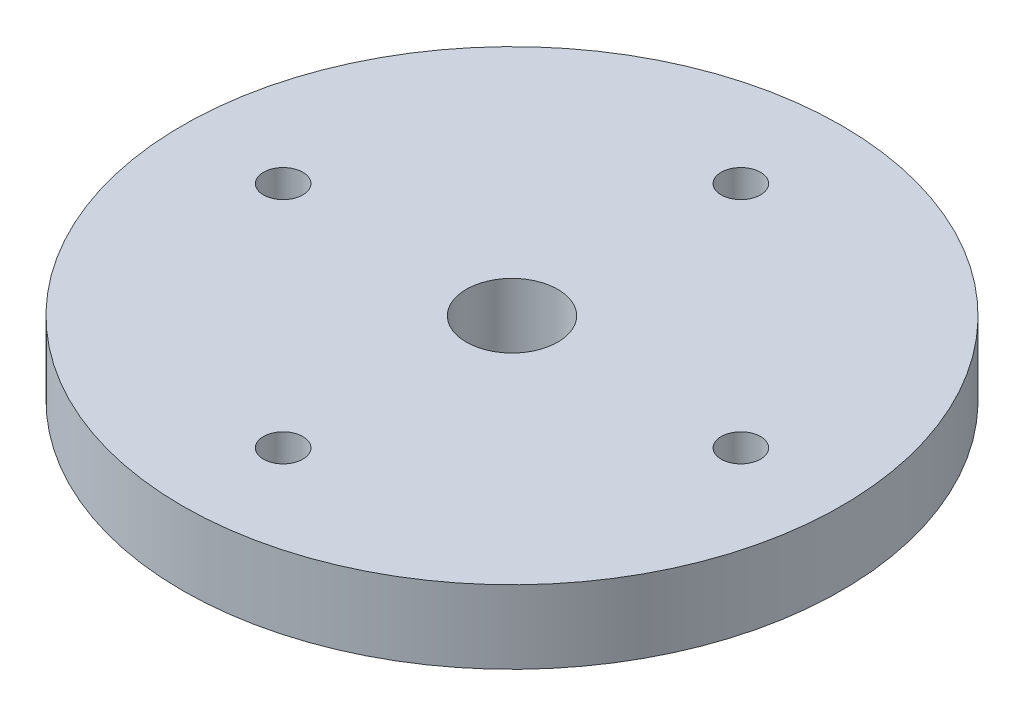
SolidWorks part; units mm, degrees
ref_plane "前视基准面" through (0, 0, 0) normal (0, 0, 1) x (1, 0, 0)
ref_plane "上视基准面" through (0, 0, 0) normal (0, 1, 0) x (1, 0, 0)
ref_plane "右视基准面" through (0, 0, 0) normal (1, 0, 0) x (0, 0, -1)
sketch "草图1" plane through (0, 0, 0) normal (0, 1, 0) x (1, 0, 0)
  circle A0 centre (0, 0) radius 36
  dimension "D1" = 72
extrude "凸台-拉伸1" add sketch "草图1" along normal blind 8
sketch "草图2" plane through (0, 8, 0) normal (0, 1, 0) x (1, 0, 0)
  circle A0 centre (0, 25) radius 2.15
  circle A1 centre (25, 0) radius 2.15
  circle A2 centre (0, -25) radius 2.15
  circle A3 centre (-25, 0) radius 2.15
  circle A4 centre (0, 0) radius 5
  point P11 (0, 0)
  dimension "D1" = 4
  dimension "D2" = 4.3
  dimension "D3" = 25
extrude "切除-拉伸1" cut sketch "草图2" against normal blind 8
